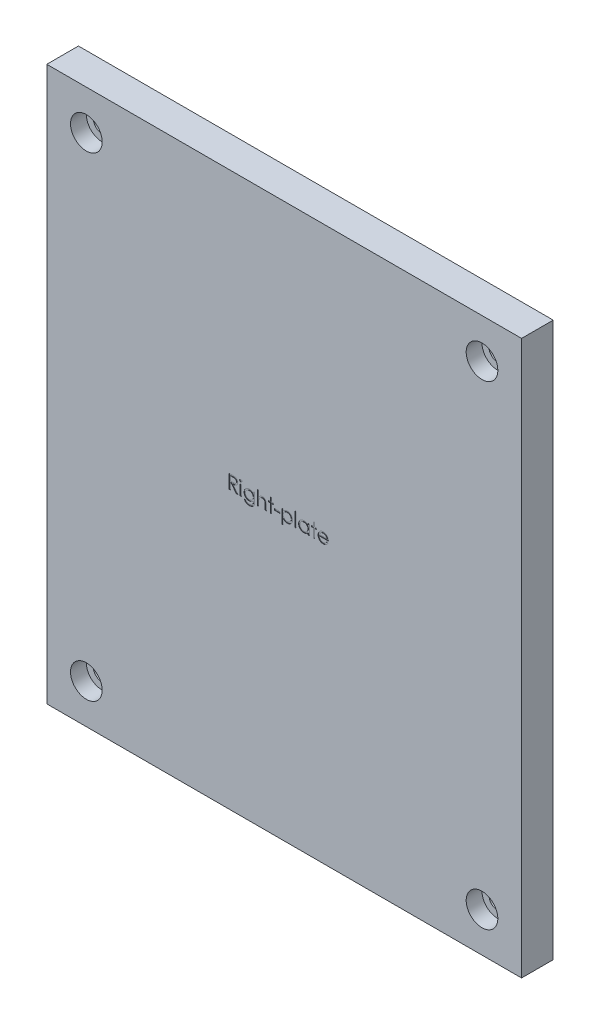
SolidWorks part; units mm, degrees
ref_plane "정면" through (0, 0, 0) normal (0, 0, 1) x (1, 0, 0)
ref_plane "윗면" through (0, 0, 0) normal (0, 1, 0) x (1, 0, 0)
ref_plane "우측면" through (0, 0, 0) normal (1, 0, 0) x (0, 0, -1)
sketch "스케치1" plane through (0, 0, 0) normal (0, 0, 1) x (1, 0, 0)
  line L1 (-60, 70) -> (60, 70)
  line L2 (-60, 70) -> (-60, -70)
  line L3 (-60, -70) -> (60, -70)
  line L4 (60, 70) -> (60, -70)
  line L5 (-60, 70) -> (60, -70) construction
  line L6 (-60, -70) -> (60, 70) construction
  point P0 (0, 0)
  dimension "D1" = 140
  dimension "D2" = 120
extrude "보스-돌출1" add sketch "스케치1" along normal blind 8
hole_wizard "M4 소켓 머리 캡 나사용 카운터보어1" positions "스케치2" profile "스케치3" counterbore size "M4" standard "KS" end condition through all
sketch "스케치2" plane through (0, 0, 8) normal (0, 0, 1) x (1, 0, 0)
  line L0 (60, 70) -> (-60, 70) construction
  line L1 (-60, 70) -> (-60, -70) construction
  line L2 (60, -70) -> (60, 70) construction
  line L3 (-60, -70) -> (60, -70) construction
  point P0 (-50, 60)
  point P7 (50, 60)
  point P9 (50, -60)
  point P11 (-50, -60)
  dimension "D1" = 10
  dimension "D2" = 10
  dimension "D3" = 10
  dimension "D4" = 10
  dimension "D5" = 10
  dimension "D6" = 10
  dimension "D7" = 10
  dimension "D8" = 10
sketch "스케치3" plane through (-50, 60, 8) normal (1, 0, 0) x (0, -1, 0)
  line L0 (0, 0) -> (0, 8)
  line L1 (0, 8) -> (2.25, 8)
  line L3 (2.25, 8) -> (2.25, 4)
  line L4 (2.25, 4) -> (4, 4)
  line L5 (4, 4) -> (4, 0)
  line L7 (4, 0) -> (0, 0)
  line L11 (0, -6.35) -> (0, 107.95) construction
  dimension "관통 구멍 지름" = 4.5
  dimension "관통 구멍 깊이" = 8
  dimension "카운터보어 지름" = 8
  dimension "카운터보어 깊이" = 4
sketch "스케치4" plane through (0, 0, 8) normal (0, 0, 1) x (1, 0, 0)
  line L0 (-38.232, 0) -> (35.2986, 0) construction
  text T0 "Right-plate"
extrude "컷-돌출1" cut sketch "스케치4" against normal blind 0.1
